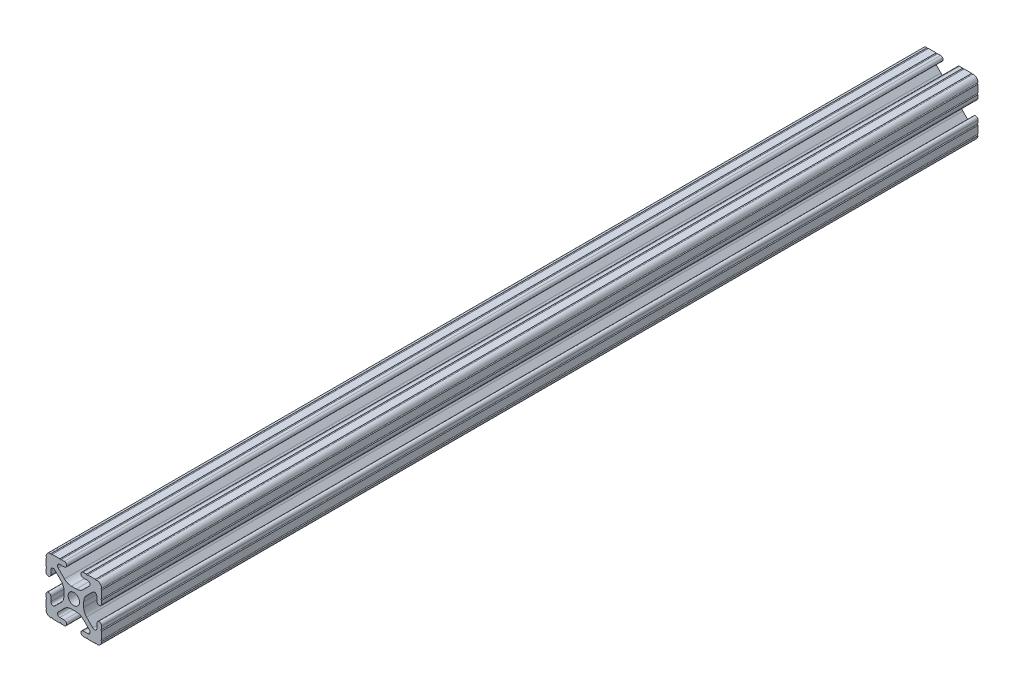
SolidWorks part; units mm, degrees
ref_plane "Front Plane" through (0, 0, 0) normal (0, 0, 1) x (1, 0, 0)
ref_plane "Top Plane" through (0, 0, 0) normal (0, 1, 0) x (1, 0, 0)
ref_plane "Right Plane" through (0, 0, 0) normal (1, 0, 0) x (0, 0, -1)
sketch "Sketch1" plane through (0, 0, 0) normal (0, 0, 1) x (1, 0, 0)
  line L0 (0, 12.7) -> (-12.7, 12.7) construction
  line L1 (-4.5085, 0) -> (-4.5085, 2.9459)
  line L2 (-6.0545, 12.7) -> (-10.1745, 12.7) construction
  line L3 (-11.6284, 12.3843) -> (-4.3434, 12.3843) construction
  line L4 (-6.3702, 10.4902) -> (-6.3702, 12.7) construction
  line L6 (-2.9459, 4.5085) -> (0, 4.5085)
  line L7 (0, 0) -> (0, 12.7) construction
  line L8 (0, 0) -> (-12.7, 0) construction
  line L9 (0.7813, 0.7813) -> (-0.7813, -0.7813) construction
  line L10 (-2.9459, 4.5085) -> (-7.1192, 8.6818)
  line L11 (-4.5085, 2.9459) -> (-8.6818, 7.1192)
  line L13 (0, 0) -> (-12.7, 12.7) construction
  line L14 (-10.4902, 12.7) -> (-4.3434, 12.7)
  line L15 (-4.3434, 12.7) -> (-4.3434, 10.4902) construction
  line L16 (-4.3434, 10.4902) -> (-6.3702, 10.4902)
  line L17 (-12.7, 10.4902) -> (-12.7, 4.3434)
  line L18 (-10.4902, 4.3434) -> (-10.4902, 6.3702)
  circle A0 centre (0, 0) radius 2.6035
  arc A1 (-4.3434, 10.4902) -> (-4.3434, 12.7) centre (-4.3434, 11.5951) ccw
  arc A2 (-7.1192, 8.6818) -> (-6.3702, 10.4902) centre (-6.3702, 9.4309) cw
  arc A3 (-8.6818, 7.1192) -> (-10.4902, 6.3702) centre (-9.4309, 6.3702) ccw
  arc A4 (-10.4902, 4.3434) -> (-12.7, 4.3434) centre (-11.5951, 4.3434) cw
  arc A5 (-10.4902, 12.7) -> (-12.7, 10.4902) centre (-10.4902, 10.4902) ccw
  arc A6 (-10.4902, 12.7) -> (-9.8588, 12.7) centre (-10.1745, 12.7) ccw
  arc A7 (-6.3702, 12.7) -> (-5.7388, 12.7) centre (-6.0545, 12.7) ccw
  arc A8 (-12.7, 6.3702) -> (-12.7, 5.7388) centre (-12.7, 6.0545) cw
  arc A9 (-12.7, 10.4902) -> (-12.7, 9.8588) centre (-12.7, 10.1745) cw
  dimension "D1" = 5.207
  dimension "D5" = 14.859
  dimension "D9" = 0
  dimension "D2" = 25.4
  dimension "D12" = 0.6314
  dimension "D10" = 2.2098
  dimension "D3" = 9.017
  dimension "D4" = 9.017
  dimension "D6" = 25.4
  dimension "D7" = 6.477
  dimension "D8" = 2.2098
  dimension "D11" = 12.7
sketch "Sketch3" plane through (0, 0, 0) normal (0, 0, 1) x (1, 0, 0)
  line L0 (-2.9459, 4.5085) -> (0, 4.5085) construction
  line L1 (-2.9459, 4.5085) -> (-7.1192, 8.6818) construction
  line L2 (-4.3434, 10.4902) -> (-6.3702, 10.4902) construction
  line L3 (-10.4902, 12.7) -> (-4.3434, 12.7) construction
  line L4 (-4.5085, 0) -> (-4.5085, 2.9459) construction
  line L5 (-4.5085, 2.9459) -> (-8.6818, 7.1192) construction
  line L6 (-10.4902, 4.3434) -> (-10.4902, 6.3702) construction
  line L7 (-12.7, 10.4902) -> (-12.7, 4.3434) construction
  line L8 (-1.1153, 4.5085) -> (1.1153, 4.5085)
  line L9 (-4.2404, 5.803) -> (-7.1192, 8.6818)
  line L10 (-4.3434, 10.4902) -> (-6.3702, 10.4902)
  line L11 (-9.8588, 12.7) -> (-6.3702, 12.7)
  line L12 (-4.5085, -1.1153) -> (-4.5085, 1.1153)
  line L13 (-5.803, 4.2404) -> (-8.6818, 7.1192)
  line L14 (-10.4902, 4.3434) -> (-10.4902, 6.3702)
  line L15 (-12.7, 9.8588) -> (-12.7, 6.3702)
  line L16 (-5.7388, 12.7) -> (-4.3434, 12.7)
  line L17 (-12.7, 5.7388) -> (-12.7, 4.3434)
  line L18 (0, 0) -> (0, 12.7) construction
  line L19 (0, 0) -> (-12.7, 0) construction
  line L20 (12.7, 5.7388) -> (12.7, 4.3434)
  line L21 (5.7388, 12.7) -> (4.3434, 12.7)
  line L22 (12.7, 9.8588) -> (12.7, 6.3702)
  line L23 (10.4902, 4.3434) -> (10.4902, 6.3702)
  line L24 (5.803, 4.2404) -> (8.6818, 7.1192)
  line L25 (4.5085, -1.1153) -> (4.5085, 1.1153)
  line L26 (9.8588, 12.7) -> (6.3702, 12.7)
  line L27 (4.3434, 10.4902) -> (6.3702, 10.4902)
  line L28 (4.2404, 5.803) -> (7.1192, 8.6818)
  line L29 (4.2404, -5.803) -> (7.1192, -8.6818)
  line L30 (4.3434, -10.4902) -> (6.3702, -10.4902)
  line L31 (9.8588, -12.7) -> (6.3702, -12.7)
  line L32 (5.803, -4.2404) -> (8.6818, -7.1192)
  line L33 (10.4902, -4.3434) -> (10.4902, -6.3702)
  line L34 (12.7, -9.8588) -> (12.7, -6.3702)
  line L35 (5.7388, -12.7) -> (4.3434, -12.7)
  line L36 (12.7, -5.7388) -> (12.7, -4.3434)
  line L37 (-12.7, -5.7388) -> (-12.7, -4.3434)
  line L38 (-5.7388, -12.7) -> (-4.3434, -12.7)
  line L39 (-12.7, -9.8588) -> (-12.7, -6.3702)
  line L40 (-10.4902, -4.3434) -> (-10.4902, -6.3702)
  line L41 (-5.803, -4.2404) -> (-8.6818, -7.1192)
  line L42 (-9.8588, -12.7) -> (-6.3702, -12.7)
  line L43 (-4.3434, -10.4902) -> (-6.3702, -10.4902)
  line L44 (-4.2404, -5.803) -> (-7.1192, -8.6818)
  line L45 (-1.1153, -4.5085) -> (1.1153, -4.5085)
  arc A0 (-10.4902, 12.7) -> (-9.8588, 12.7) centre (-10.1745, 12.7) ccw construction
  arc A1 (-6.3702, 10.4902) -> (-7.1192, 8.6818) centre (-6.3702, 9.4309) ccw construction
  arc A2 (-4.3434, 10.4902) -> (-4.3434, 12.7) centre (-4.3434, 11.5951) ccw construction
  arc A3 (-8.6818, 7.1192) -> (-10.4902, 6.3702) centre (-9.4309, 6.3702) ccw construction
  arc A4 (-12.7, 4.3434) -> (-10.4902, 4.3434) centre (-11.5951, 4.3434) ccw construction
  arc A5 (-6.3702, 12.7) -> (-5.7388, 12.7) centre (-6.0545, 12.7) ccw construction
  arc A6 (-10.4902, 12.7) -> (-12.7, 10.4902) centre (-10.4902, 10.4902) ccw construction
  arc A7 (-12.7, 9.8588) -> (-12.7, 10.4902) centre (-12.7, 10.1745) ccw construction
  arc A8 (-12.7, 5.7388) -> (-12.7, 6.3702) centre (-12.7, 6.0545) ccw construction
  arc A9 (-10.4902, 12.7) -> (-9.8588, 12.7) centre (-10.1745, 12.7) ccw
  arc A10 (-6.3702, 10.4902) -> (-7.1192, 8.6818) centre (-6.3702, 9.4309) ccw
  arc A11 (-4.3434, 10.4902) -> (-4.3434, 12.7) centre (-4.3434, 11.5951) ccw
  arc A12 (-8.6818, 7.1192) -> (-10.4902, 6.3702) centre (-9.4309, 6.3702) ccw
  arc A13 (-12.7, 4.3434) -> (-10.4902, 4.3434) centre (-11.5951, 4.3434) ccw
  arc A14 (-6.3702, 12.7) -> (-5.7388, 12.7) centre (-6.0545, 12.7) ccw
  arc A15 (-10.4902, 12.7) -> (-12.7, 10.4902) centre (-10.4902, 10.4902) ccw
  arc A16 (-12.7, 9.8588) -> (-12.7, 10.4902) centre (-12.7, 10.1745) ccw
  arc A17 (-12.7, 5.7388) -> (-12.7, 6.3702) centre (-12.7, 6.0545) ccw
  arc A18 (-1.1153, 4.5085) -> (-4.2404, 5.803) centre (-1.1153, 8.9281) cw
  arc A19 (4.5085, 1.1153) -> (5.803, 4.2404) centre (8.9281, 1.1153) cw
  arc A20 (1.1153, 4.5085) -> (4.2404, 5.803) centre (1.1153, 8.9281) ccw
  arc A21 (-4.5085, 1.1153) -> (-5.803, 4.2404) centre (-8.9281, 1.1153) ccw
  arc A22 (12.7, 5.7388) -> (12.7, 6.3702) centre (12.7, 6.0545) cw
  arc A23 (12.7, 9.8588) -> (12.7, 10.4902) centre (12.7, 10.1745) cw
  arc A24 (10.4902, 12.7) -> (12.7, 10.4902) centre (10.4902, 10.4902) cw
  arc A25 (6.3702, 12.7) -> (5.7388, 12.7) centre (6.0545, 12.7) cw
  arc A26 (12.7, 4.3434) -> (10.4902, 4.3434) centre (11.5951, 4.3434) cw
  arc A27 (8.6818, 7.1192) -> (10.4902, 6.3702) centre (9.4309, 6.3702) cw
  arc A28 (4.3434, 10.4902) -> (4.3434, 12.7) centre (4.3434, 11.5951) cw
  arc A29 (6.3702, 10.4902) -> (7.1192, 8.6818) centre (6.3702, 9.4309) cw
  arc A30 (10.4902, 12.7) -> (9.8588, 12.7) centre (10.1745, 12.7) cw
  arc A31 (10.4902, -12.7) -> (9.8588, -12.7) centre (10.1745, -12.7) ccw
  arc A32 (6.3702, -10.4902) -> (7.1192, -8.6818) centre (6.3702, -9.4309) ccw
  arc A33 (4.3434, -10.4902) -> (4.3434, -12.7) centre (4.3434, -11.5951) ccw
  arc A34 (8.6818, -7.1192) -> (10.4902, -6.3702) centre (9.4309, -6.3702) ccw
  arc A35 (12.7, -4.3434) -> (10.4902, -4.3434) centre (11.5951, -4.3434) ccw
  arc A36 (6.3702, -12.7) -> (5.7388, -12.7) centre (6.0545, -12.7) ccw
  arc A37 (10.4902, -12.7) -> (12.7, -10.4902) centre (10.4902, -10.4902) ccw
  arc A38 (12.7, -9.8588) -> (12.7, -10.4902) centre (12.7, -10.1745) ccw
  arc A39 (12.7, -5.7388) -> (12.7, -6.3702) centre (12.7, -6.0545) ccw
  arc A40 (-4.5085, -1.1153) -> (-5.803, -4.2404) centre (-8.9281, -1.1153) cw
  arc A41 (1.1153, -4.5085) -> (4.2404, -5.803) centre (1.1153, -8.9281) cw
  arc A42 (4.5085, -1.1153) -> (5.803, -4.2404) centre (8.9281, -1.1153) ccw
  arc A43 (-1.1153, -4.5085) -> (-4.2404, -5.803) centre (-1.1153, -8.9281) ccw
  arc A44 (-12.7, -5.7388) -> (-12.7, -6.3702) centre (-12.7, -6.0545) cw
  arc A45 (-12.7, -9.8588) -> (-12.7, -10.4902) centre (-12.7, -10.1745) cw
  arc A46 (-10.4902, -12.7) -> (-12.7, -10.4902) centre (-10.4902, -10.4902) cw
  arc A47 (-6.3702, -12.7) -> (-5.7388, -12.7) centre (-6.0545, -12.7) cw
  arc A48 (-12.7, -4.3434) -> (-10.4902, -4.3434) centre (-11.5951, -4.3434) cw
  arc A49 (-8.6818, -7.1192) -> (-10.4902, -6.3702) centre (-9.4309, -6.3702) cw
  arc A50 (-4.3434, -10.4902) -> (-4.3434, -12.7) centre (-4.3434, -11.5951) cw
  arc A51 (-6.3702, -10.4902) -> (-7.1192, -8.6818) centre (-6.3702, -9.4309) cw
  arc A52 (-10.4902, -12.7) -> (-9.8588, -12.7) centre (-10.1745, -12.7) cw
  circle A53 centre (0, 0) radius 2.6035 construction
  circle A54 centre (0, 0) radius 2.6035
  point P135 (4.5085, 0)
  dimension "D2" = 4.4196
extrude "Extrude1" add sketch "Sketch3" along normal mid plane 400.05
equation "\"D10@Sketch1\" = \"D8@Sketch1\""
equation "\"D11@Sketch1\" = \"D6@Sketch1\"/2"
equation "\"D12@Sketch1\" = \"D8@Sketch1\"/3.5"
equation "\"D2@Sketch3\" = \"D8@Sketch1\"*2"
